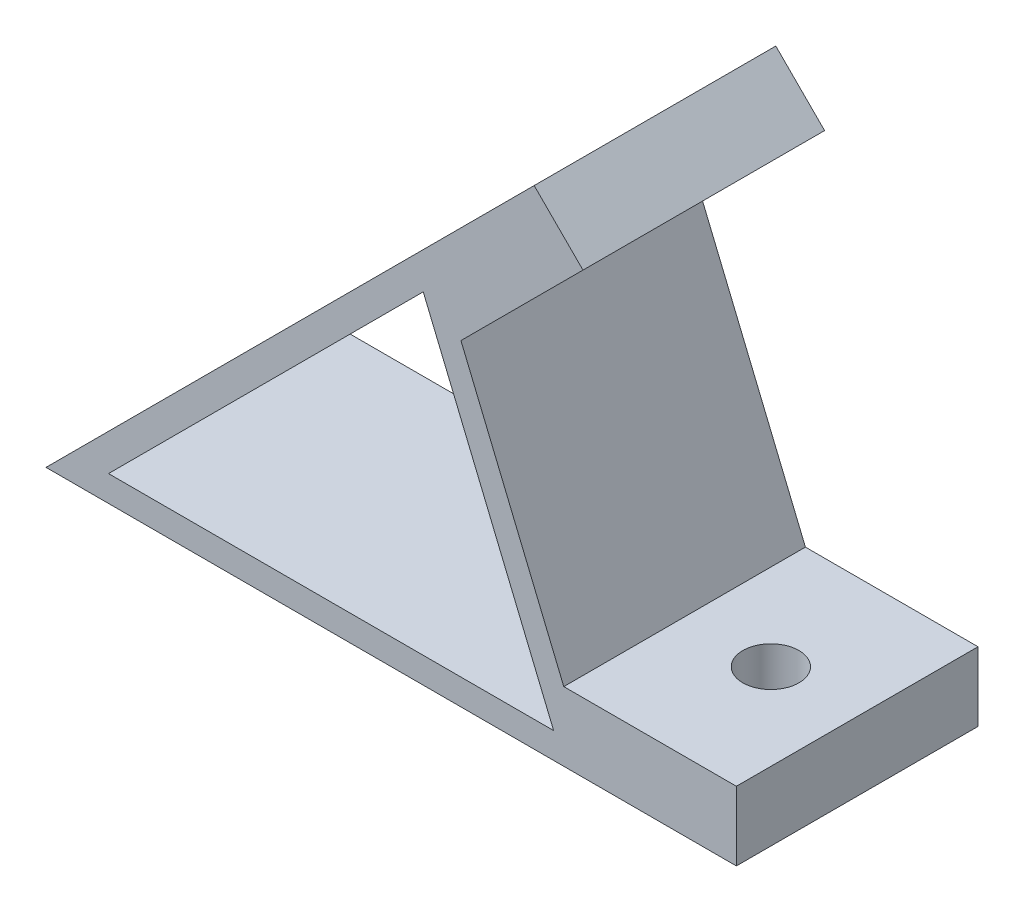
SolidWorks part; units mm, degrees
ref_plane "前视基准面" through (0, 0, 0) normal (0, 0, 1) x (1, 0, 0)
ref_plane "上视基准面" through (0, 0, 0) normal (0, 1, 0) x (1, 0, 0)
ref_plane "右视基准面" through (0, 0, 0) normal (1, 0, 0) x (0, 0, -1)
sketch "草图2" plane through (0, 0, 0) normal (0, 0, 1) x (1, 0, 0)
  line L0 (56.5685, 56.5685) -> (0, 0)
  line L1 (0, 0) -> (80, 0)
  line L2 (56.5685, 56.5685) -> (62.2254, 50.9117)
  line L3 (62.2254, 50.9117) -> (48.0833, 36.7696)
  line L4 (48.0833, 36.7696) -> (60, 8)
  line L5 (60, 8) -> (80, 8)
  line L6 (80, 8) -> (80, 0)
  line L7 (7.2426, 3) -> (43.7161, 39.4735)
  line L8 (43.7161, 39.4735) -> (58.8239, 3)
  line L9 (58.8239, 3) -> (7.2426, 3)
  dimension "D1" = 45
  dimension "D2" = 80
  dimension "D3" = 8
  dimension "D4" = 8
  dimension "D5" = 3
  dimension "D6" = 3
  dimension "D7" = 3
  dimension "D8" = 20
extrude "凸台-拉伸1" add sketch "草图2" along normal blind 28
sketch "草图3" plane through (0, 8, 0) normal (0, 1, 0) x (1, 0, 0)
  line L0 (80, -14) -> (68.422, -14) construction
  line L1 (80, -28) -> (80, 0) construction
  circle A0 centre (70, -14) radius 3.25
  point P6 (73.7926, -14)
  dimension "D1" = 10
  dimension "D2" = 6.5
extrude "切除-拉伸1" cut sketch "草图3" against normal blind 10
sketch "草图4" plane through (5.6569, -5.6569, 0) normal (0.7071, -0.7071, 0) x (0, 0, -1)
  line L0 (-14, 80) -> (-14, 65.9991) construction
  line L1 (-28, 80) -> (0, 80) construction
  circle A0 centre (-14, 70) radius 3.25
  dimension "D1" = 6.5
  dimension "D2" = 10
extrude "切除-拉伸2" cut sketch "草图4" against normal blind 10
